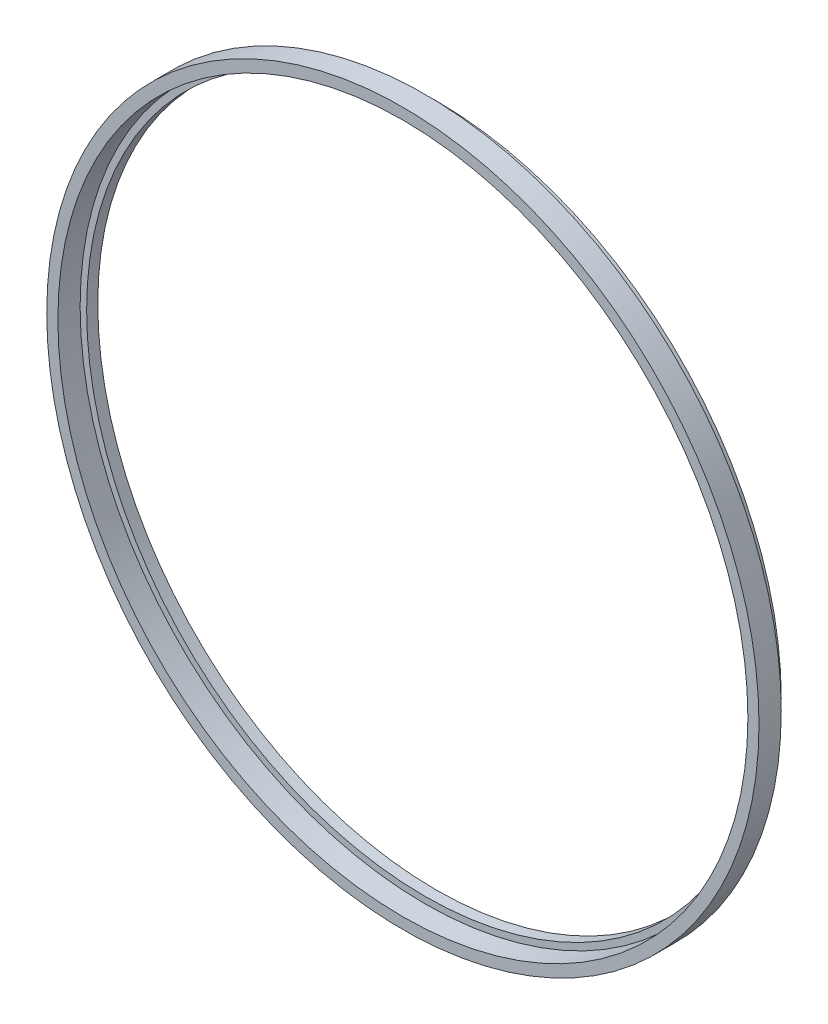
SolidWorks part; units mm, degrees
ref_plane "Front Plane" through (0, 0, 0) normal (0, 0, 1) x (1, 0, 0)
ref_plane "Top Plane" through (0, 0, 0) normal (0, 1, 0) x (1, 0, 0)
ref_plane "Right Plane" through (0, 0, 0) normal (1, 0, 0) x (0, 0, -1)
sketch "Sketch1" plane through (0, 0, 0) normal (0, 0, 1) x (1, 0, 0)
  circle A0 centre (0, 0) radius 64
  circle A1 centre (0, 0) radius 62
  dimension "D1" = 2
  dimension "D2" = 128
extrude "Boss-Extrude1" add sketch "Sketch1" along normal blind 4
sketch "Sketch2" plane through (0, 0, 0) normal (0, 0, -1) x (-1, 0, 0)
  circle A0 centre (0, 0) radius 60.83
  circle A1 centre (0, 0) radius 62 construction
  circle A2 centre (0, 0) radius 62
  dimension "D1" = 121.66
extrude "Boss-Extrude2" add sketch "Sketch2" along normal blind 2
